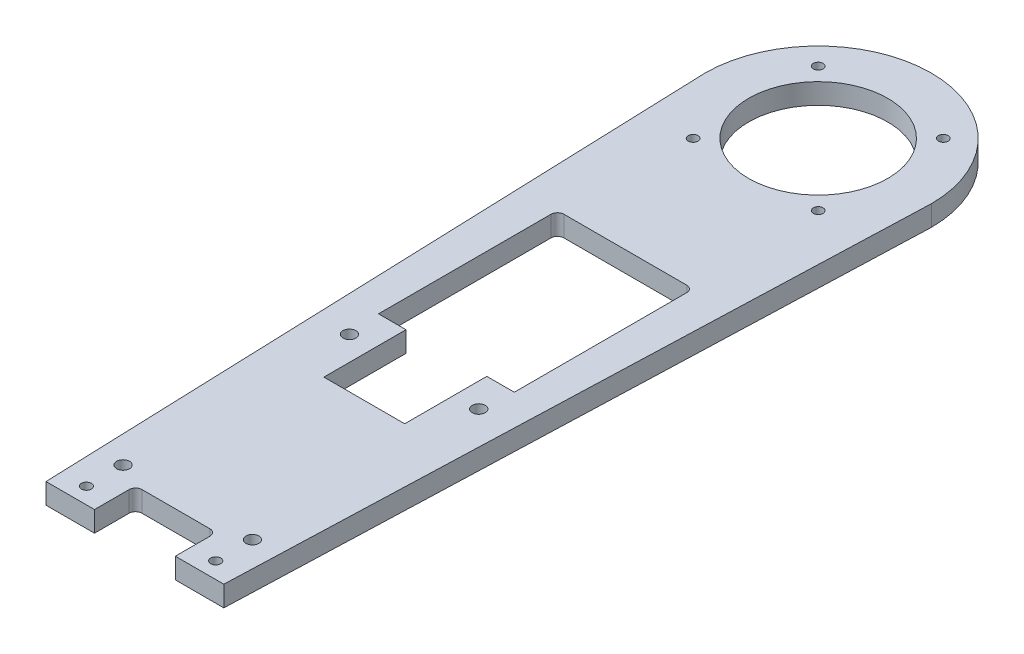
SolidWorks part; units mm, degrees
ref_plane "Front Plane" through (0, 0, 0) normal (0, 0, 1) x (1, 0, 0)
ref_plane "Top Plane" through (0, 0, 0) normal (0, 1, 0) x (1, 0, 0)
ref_plane "Right Plane" through (0, 0, 0) normal (1, 0, 0) x (0, 0, -1)
sketch "Sketch1" plane through (0, 0, 0) normal (0, 1, 0) x (1, 0, 0)
  line L0 (-35, 0) -> (-27.5, -211.35)
  line L1 (-27.5, -211.35) -> (27.5, -211.35)
  line L2 (27.5, -211.35) -> (35, 0)
  circle A0 centre (0, 0) radius 35
  point P3 (0, -211.35)
  dimension "D1" = 70
  dimension "D2" = 55
  dimension "D3" = 211.35
extrude "Boss-Extrude1" add sketch "Sketch1" along normal mid plane 6.35
sketch "Sketch2" plane through (0, 3.175, 0) normal (0, 1, 0) x (1, 0, 0)
  circle A0 centre (0, 0) radius 21.5
  dimension "D1" = 43
extrude "Cut-Extrude1" cut sketch "Sketch2" against normal through all
sketch "Sketch3" plane through (0, 3.175, 0) normal (0, 1, 0) x (1, 0, 0)
  line L1 (21, -115) -> (-21, -115)
  line L2 (21, -115) -> (21, -59.65)
  line L3 (21, -59.65) -> (-21, -59.65)
  line L4 (-21, -115) -> (-21, -59.65)
  line L5 (21, -115) -> (-21, -59.65) construction
  line L6 (21, -59.65) -> (-21, -115) construction
  line L11 (-27.5, -211.35) -> (27.5, -211.35) construction
  line L13 (12.5, -211.35) -> (-12.5, -211.35)
  line L14 (12.5, -211.35) -> (12.5, -115)
  line L15 (12.5, -115) -> (-12.5, -115)
  line L16 (-12.5, -211.35) -> (-12.5, -115)
  line L17 (12.5, -211.35) -> (-12.5, -115) construction
  line L18 (12.5, -115) -> (-12.5, -211.35) construction
  point P0 (0, -87.325)
  point P8 (0, -163.175)
  line M13 (-27.5, -211.35) -> (27.5, -211.35)
  dimension "D1" = 96.35
  dimension "D2" = 42
  dimension "D3" = 25
  dimension "48" = 55.35
extrude "Cut-Extrude2" cut sketch "Sketch3" against normal through all contours L4 L1 L2 L3 | L16 L14 L1 M13
sketch "Sketch4" plane through (0, 3.175, 0) normal (0, 1, 0) x (1, 0, 0)
  line L0 (-19.35, 19.35) -> (-19.35, -19.35) construction
  line L1 (-19.35, -19.35) -> (19.35, -19.35) construction
  line L2 (19.35, -19.35) -> (19.35, 19.35) construction
  line L3 (19.35, 19.35) -> (-19.35, 19.35) construction
  circle A0 centre (-19.35, 19.35) radius 1.5
  circle A1 centre (19.35, 19.35) radius 1.5
  circle A2 centre (19.35, -19.35) radius 1.5
  circle A3 centre (-19.35, -19.35) radius 1.5
  point P8 (19.35, 0)
  point P9 (0, 19.35)
  dimension "D2" = 3
  dimension "D1" = 38.7
extrude "Cut-Extrude3" cut sketch "Sketch4" against normal through all
sketch "Sketch5" plane through (0, 3.175, 0) normal (0, 1, 0) x (1, 0, 0)
  line L0 (21, -115) -> (12.5, -115) construction
  line L2 (20, -195) -> (-20, -195) construction
  line L6 (-29.3222, -160) -> (29.3222, -160) construction
  line L7 (-35, 0) -> (-27.5, -211.35) construction
  line L8 (27.5, -211.35) -> (35, 0) construction
  circle A2 centre (-20, -195) radius 2
  circle A3 centre (20, -195) radius 2
  circle A4 centre (20, -125) radius 2
  circle A5 centre (-20, -125) radius 2
  point P13 (0, -195)
  dimension "D1" = 80
  dimension "D3" = 4
  dimension "D2" = 40
  dimension "D6" = 35
extrude "Cut-Extrude4" cut sketch "Sketch5" against normal through all
sketch "Sketch7" plane through (0, -3.175, 0) normal (0, -1, 0) x (1, 0, 0)
  line L0 (-20, 206.35) -> (20, 206.35) construction
  line L2 (-27.5, 211.35) -> (-12.5, 211.35) construction
  circle A0 centre (-20, 206.35) radius 1.55
  circle A1 centre (20, 206.35) radius 1.55
  point P4 (0, 206.35)
  dimension "D1" = 3.1
  dimension "D2" = 5
  dimension "D3" = 40
extrude "Cut-Extrude6" cut sketch "Sketch7" against normal through all
sketch "Sketch8" plane through (0, 3.175, 0) normal (0, 1, 0) x (1, 0, 0)
  line L0 (-12.5, -211.35) -> (-12.5, -115) construction
  line L1 (-12.5, -140.4) -> (12.5, -140.4)
  line L2 (-12.5, -140.4) -> (-12.5, -198.65)
  line L3 (-12.5, -198.65) -> (12.5, -198.65)
  line L4 (12.5, -140.4) -> (12.5, -198.65)
  line L6 (21, -115) -> (12.5, -115) construction
  line L8 (12.5, -211.35) -> (27.5, -211.35) construction
  line L9 (12.5, -211.35) -> (12.5, -115) construction
  point P10 (16.75, -115)
  dimension "D2" = 12.7
  dimension "D1" = 25.4
extrude "Boss-Extrude2" add sketch "Sketch8" against normal up to surface (6.35 mm away) up to face at (-20, -3.175, 204.8)
fillet "Fillet1" radius 2 4 edges at (21, 0, 59.65) (-21, 0, 59.65) (-12.5, 0, 198.65) (12.5, 0, 198.65)
